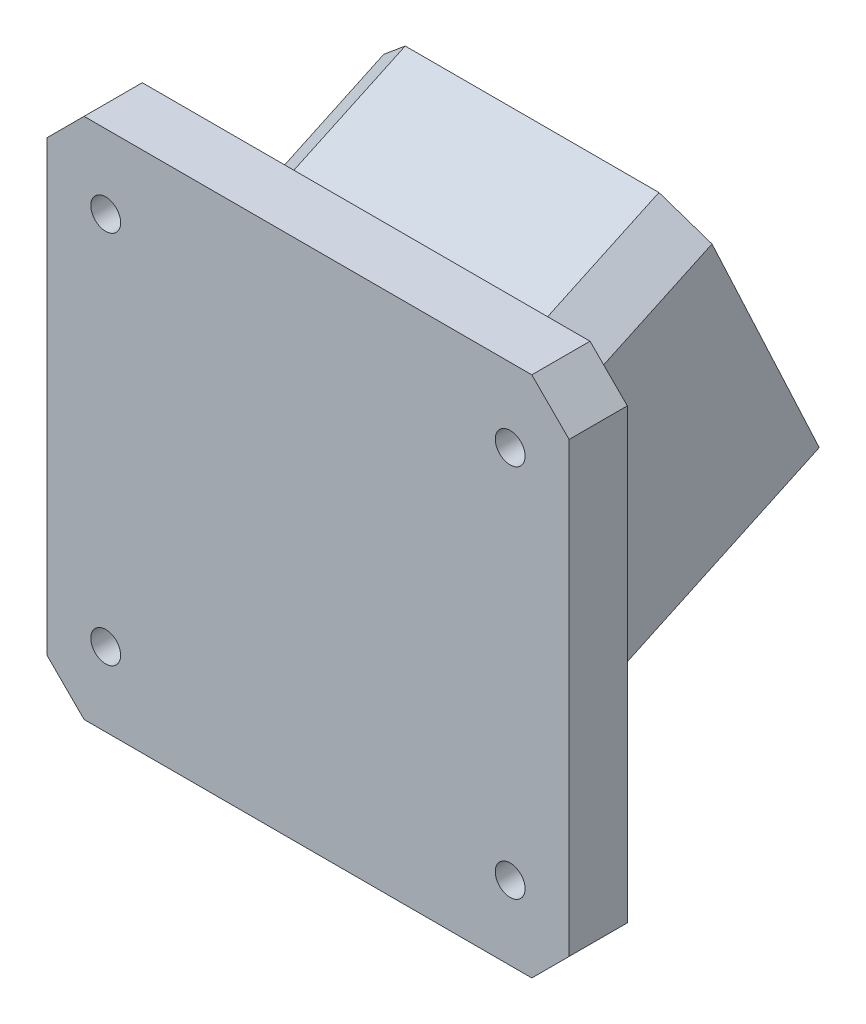
SolidWorks part; units mm, degrees
ref_plane "Front Plane" through (0, 0, 0) normal (0, 0, 1) x (1, 0, 0)
ref_plane "Top Plane" through (0, 0, 0) normal (0, 1, 0) x (1, 0, 0)
ref_plane "Right Plane" through (0, 0, 0) normal (1, 0, 0) x (0, 0, -1)
sketch "Sketch1" plane through (0, 0, 0) normal (0, 0, 1) x (1, 0, 0)
  line L0 (17.5, 15) -> (15, 17.5)
  line L1 (15, -17.5) -> (-15, -17.5)
  line L2 (17.5, -15) -> (17.5, 15)
  line L3 (15, 17.5) -> (-15, 17.5)
  line L4 (-17.5, -15) -> (-17.5, 15)
  line L5 (17.5, -17.5) -> (-17.5, 17.5) construction
  line L6 (17.5, 17.5) -> (-17.5, -17.5) construction
  line L7 (15, -17.5) -> (17.5, -15)
  line L8 (-15, 17.5) -> (-17.5, 15)
  line L9 (-15, -17.5) -> (-17.5, -15)
  point P0 (0, 0)
  dimension "D1" = 35
  dimension "D2" = 35
extrude "Boss-Extrude1" add sketch "Sketch1" along normal blind 3.9
ref_plane "Plane1" through (0, 0, 13.9) normal (0, 0, 1) x (1, 0, 0)
sketch "Sketch2" plane through (0, 0, 13.9) normal (0, 0, 1) x (1, 0, 0)
  line L0 (0, 0) -> (0, -12.55) construction
  line L1 (0, 0) -> (0, 12.55) construction
  line L2 (-12.55, -12.55) -> (-13.55, -12.55) construction
  line L3 (12.55, -12.55) -> (13.55, -12.55) construction
  line L4 (-13.55, -12.55) -> (-13.55, 12.55) construction
  line L5 (-13.55, 12.55) -> (-12.55, 12.55) construction
  circle A1 centre (-13.55, 12.55) radius 1
  circle A2 centre (-13.55, -12.55) radius 1
  circle A3 centre (13.55, 12.55) radius 1
  circle A4 centre (13.55, -12.55) radius 1
  dimension "D6" = 2
  dimension "D7" = 2
  dimension "D8" = 2
  dimension "D9" = 2
  dimension "D1" = 12.55
  dimension "D2" = 12.55
  dimension "D3" = 13.55
  dimension "D4" = 13.55
extrude "Cut-Extrude3" cut sketch "Sketch2" against normal through all
ref_plane "Plane6" through (0, 3.1256, -6.7029) normal (0, 0.4226, -0.9063) x (-1, 0, 0)
sketch "Sketch161" plane through (0, 3.1256, -6.7029) normal (0, 0.4226, -0.9063) x (-1, 0, 0)
  line L0 (-8.5, 11) -> (-11, 8.5)
  line L1 (8.5, -11) -> (-8.5, -11)
  line L2 (11, -8.5) -> (11, 8.5)
  line L3 (8.5, 11) -> (-8.5, 11)
  line L4 (-11, -8.5) -> (-11, 8.5)
  line L5 (11, -11) -> (-11, 11) construction
  line L6 (11, 11) -> (-11, -11) construction
  line L7 (-8.5, -11) -> (-11, -8.5)
  line L8 (8.5, -11) -> (11, -8.5)
  line L9 (11, 8.5) -> (8.5, 11)
  circle A0 centre (0, 0) radius 8
  point P0 (0, 0)
  dimension "D3" = 16
  dimension "D1" = 22
  dimension "D2" = 22
extrude "Boss-Extrude11" add sketch "Sketch161" against normal blind 15 and the other way blind 10
ref_plane "Plane7" through (0, 0, 13.9) normal (0, 0, 1) x (1, 0, 0)
sketch "Sketch162" plane through (0, 0, 13.9) normal (0, 0, 1) x (1, 0, 0)
  line L0 (-17.5, 15) -> (-15, 17.5)
  line L1 (-15, 17.5) -> (15, 17.5)
  line L2 (15, 17.5) -> (17.5, 15)
  line L3 (17.5, 15) -> (17.5, -15)
  line L4 (17.5, -15) -> (15, -17.5)
  line L5 (15, -17.5) -> (-15, -17.5)
  line L6 (-15, -17.5) -> (-17.5, -15)
  line L7 (-17.5, -15) -> (-17.5, 15)
extrude "Cut-Extrude5" cut sketch "Sketch162" against normal blind 10
